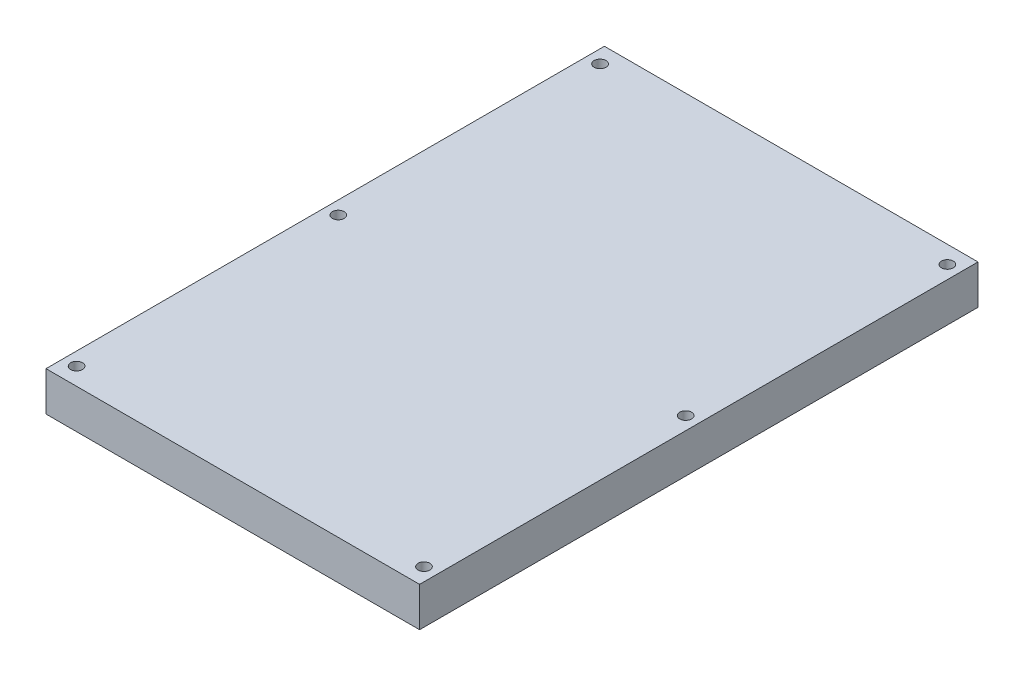
SolidWorks part; units mm, degrees
ref_plane "Front" through (0, 0, 0) normal (0, 0, 1) x (1, 0, 0)
ref_plane "Top" through (0, 0, 0) normal (0, 1, 0) x (1, 0, 0)
ref_plane "Right" through (0, 0, 0) normal (1, 0, 0) x (0, 0, -1)
sketch "Sketch1" plane through (0, 0, 0) normal (0, 1, 0) x (1, 0, 0)
  line L1 (0, 0) -> (85.5, 0)
  line L2 (0, 0) -> (0, 127.8)
  line L3 (0, 127.8) -> (85.5, 127.8)
  line L4 (85.5, 0) -> (85.5, 127.8)
  dimension "D1" = 85.5
  dimension "D2" = 127.8
extrude "Boss-Extrude1" add sketch "Sketch1" along normal blind 9
hole_wizard "Tap Drill for #6-32 Tap1" positions "Sketch2" profile "Sketch3" hole size "#6-32" standard "ANSI Inch" end condition through all
sketch "Sketch2" plane through (0, 9, 0) normal (0, 1, 0) x (1, 0, 0)
  line L0 (0, 0) -> (85.5, 0) construction
  line L1 (85.5, 0) -> (85.5, 127.8) construction
  point P0 (82.5, 4)
  dimension "D1" = 4
  dimension "D2" = 3
sketch "Sketch3" plane through (82.5, 9, -4) normal (1, 0, 0) x (0, 0, 1)
  line L0 (0, 0) -> (0, 9)
  line L1 (0, 9) -> (1.3525, 9)
  line L2 (1.3525, 9) -> (1.3525, 0)
  line L5 (1.3525, 0) -> (0, 0)
  line L11 (0, -6.35) -> (0, 107.95) construction
  dimension "Thru Hole Dia." = 2.7051
  dimension "Thru Hole Depth" = 9
pattern_linear "LPattern1" count 3 spacing 59.9 along (0, 0, -1) of "Tap Drill for #6-32 Tap1"
ref_plane "Plane1" through (42.75, 0, 0) normal (1, 0, 0) x (0, 0, -1)
mirror "Mirror1" about plane through (42.75, 0, 0) normal (1, 0, 0) of "LPattern1", "Tap Drill for #6-32 Tap1"
